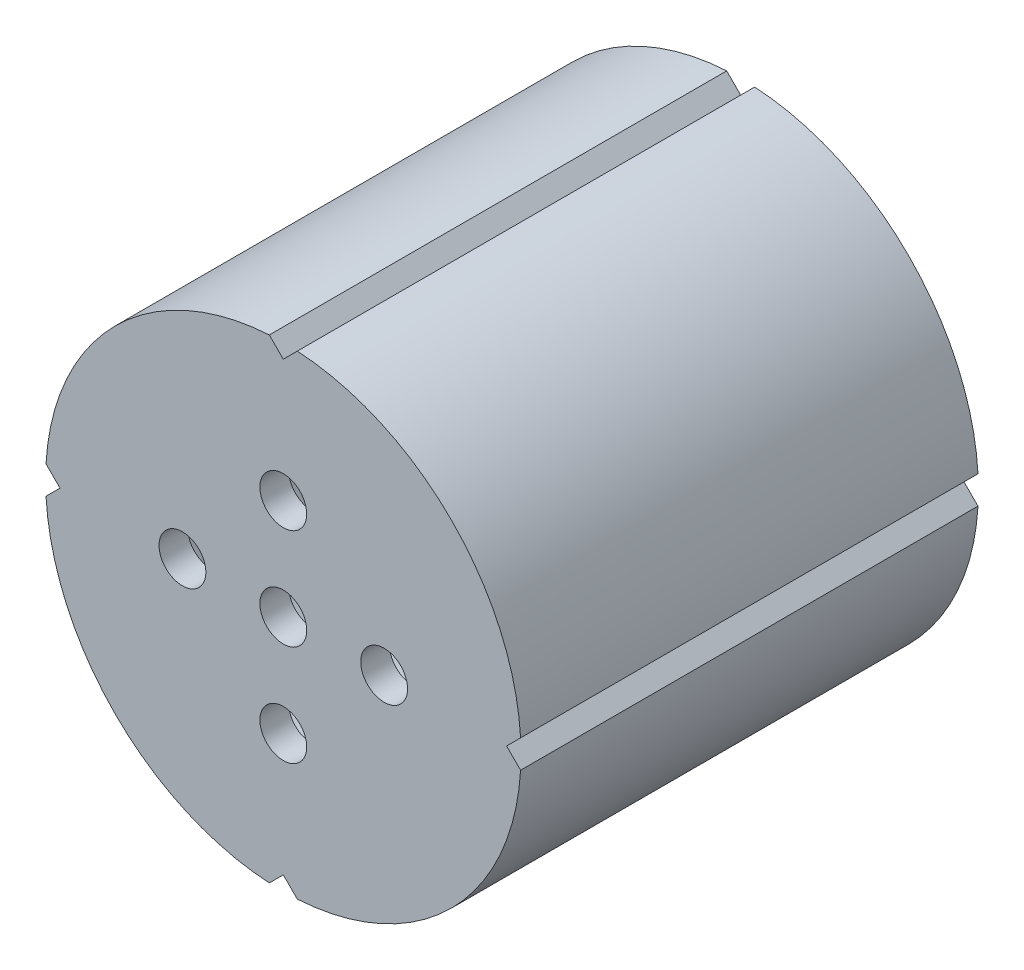
SolidWorks part; units mm, degrees
ref_plane "Alzado" through (0, 0, 0) normal (0, 0, 1) x (1, 0, 0)
ref_plane "Planta" through (0, 0, 0) normal (0, 1, 0) x (1, 0, 0)
ref_plane "Vista lateral" through (0, 0, 0) normal (1, 0, 0) x (0, 0, -1)
sketch "Croquis1" plane through (0, 0, 0) normal (0, 0, 1) x (1, 0, 0)
  line L0 (19.9763, -25.8) -> (20.4763, -25.8) construction
  line L1 (4.9763, -10.8) -> (4.9763, -10.3) construction
  line L4 (21.4477, -26.7714) -> (20.4763, -25.8)
  line L6 (21.4477, -24.8286) -> (20.4763, -25.8)
  line L7 (-10.0237, -25.8) -> (-10.5237, -25.8) construction
  line L8 (4.9763, -40.8) -> (4.9763, -41.3) construction
  line L12 (5.9477, -42.2714) -> (4.9763, -41.3)
  line L13 (4.005, -42.2714) -> (4.9763, -41.3)
  line L17 (-11.495, -26.7714) -> (-10.5237, -25.8)
  line L18 (-11.495, -24.8286) -> (-10.5237, -25.8)
  line L19 (5.9477, -9.3286) -> (4.9763, -10.3)
  line L22 (4.9763, -10.3) -> (4.005, -9.3286)
  line L23 (4.9763, -25.8) -> (4.9763, -18.8) construction
  line L24 (4.9763, -25.8) -> (11.9763, -25.8) construction
  line L25 (4.9763, -25.8) -> (4.9763, -32.8) construction
  line L26 (4.9763, -25.8) -> (-2.0237, -25.8) construction
  line L27 (0, 0) -> (4.005, 0) construction
  line L28 (4.005, 0) -> (4.005, -9.3286) construction
  arc A2 (4.005, -9.3286) -> (-11.495, -24.8286) centre (4.9763, -25.8) ccw
  arc A3 (21.4477, -24.8286) -> (5.9477, -9.3286) centre (4.9763, -25.8) ccw
  arc A4 (5.9477, -42.2714) -> (21.4477, -26.7714) centre (4.9763, -25.8) ccw
  arc A5 (-11.495, -26.7714) -> (4.005, -42.2714) centre (4.9763, -25.8) ccw
  circle A6 centre (4.9763, -25.8) radius 1.625
  circle A7 centre (-2.0237, -25.8) radius 1.625
  circle A8 centre (4.9763, -18.8) radius 1.625
  circle A9 centre (11.9763, -25.8) radius 1.625
  circle A10 centre (4.9763, -32.8) radius 1.625
  point P32 (5.8749, -42.2645)
  dimension "D1" = 3.25
  dimension "D2" = 30
  dimension "D3" = 9.3286
  dimension "D4" = 4.005
  dimension "D5" = 7
  dimension "D6" = 0.5
  dimension "D7" = 1.3737
  dimension "D8" = 1.9428
  dimension "D9" = 1.3737
  dimension "D10" = 1.9428
  dimension "D11" = 1.9428
extrude "Saliente-Extruir1" add sketch "Croquis1" along normal blind 2
sketch "Croquis3" plane through (0, 0, 0) normal (0, 0, -1) x (-1, 0, 0)
  line L0 (-5.9477, -9.3286) -> (-4.9763, -10.3)
  line L1 (-4.9763, -10.3) -> (-4.005, -9.3286)
  line L2 (-21.4477, -24.8286) -> (-20.4763, -25.8)
  line L3 (-20.4763, -25.8) -> (-21.4477, -26.7714)
  line L4 (-4.005, -42.2714) -> (-4.9763, -41.3)
  line L5 (-4.9763, -41.3) -> (-5.9477, -42.2714)
  line L6 (11.495, -24.8286) -> (10.5237, -25.8)
  line L7 (10.5237, -25.8) -> (11.495, -26.7714)
  arc A0 (-4.005, -9.3286) -> (11.495, -24.8286) centre (-4.9763, -25.8) cw
  arc A1 (11.495, -26.7714) -> (-4.005, -42.2714) centre (-4.9763, -25.8) cw
  arc A2 (-5.9477, -42.2714) -> (-21.4477, -26.7714) centre (-4.9763, -25.8) cw
  arc A3 (-21.4477, -24.8286) -> (-5.9477, -9.3286) centre (-4.9763, -25.8) cw
  circle A4 centre (-4.9763, -25.8) radius 15
  dimension "D1" = 30
extrude "Saliente-Extruir2" add sketch "Croquis3" along normal blind 29.75
